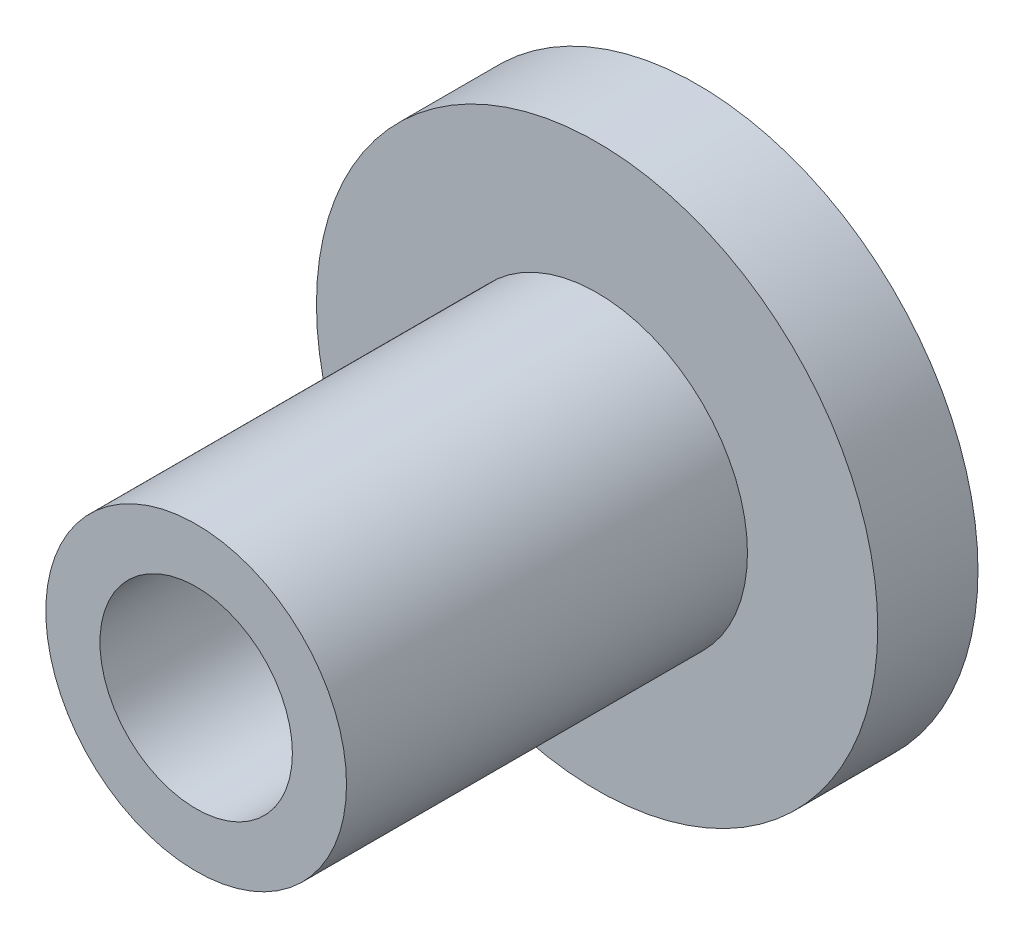
SolidWorks part; units mm, degrees
ref_plane "前视基准面" through (0, 0, 0) normal (0, 0, 1) x (1, 0, 0)
ref_plane "上视基准面" through (0, 0, 0) normal (0, 1, 0) x (1, 0, 0)
ref_plane "右视基准面" through (0, 0, 0) normal (1, 0, 0) x (0, 0, -1)
other "Configuration Table"
sketch "Sketch1" plane through (0, 0, 0) normal (0, 0, 1) x (1, 0, 0)
  circle A0 centre (0, 0) radius 7
  dimension "D1" = 14
extrude "Boss-Extrude1" add sketch "Sketch1" along normal blind 2.5
sketch "Sketch2" plane through (0, 0, 2.5) normal (0, 0, 1) x (1, 0, 0)
  circle A0 centre (0, 0) radius 3.75
  dimension "D1" = 7.5
extrude "Boss-Extrude2" add sketch "Sketch2" along normal blind 10
sketch "Sketch3" plane through (0, 0, 12.5) normal (0, 0, 1) x (1, 0, 0)
  circle A5 centre (0, 0) radius 2.4
  dimension "D1" = 4.8
extrude "Cut-Extrude1" cut sketch "Sketch3" against normal blind 5
